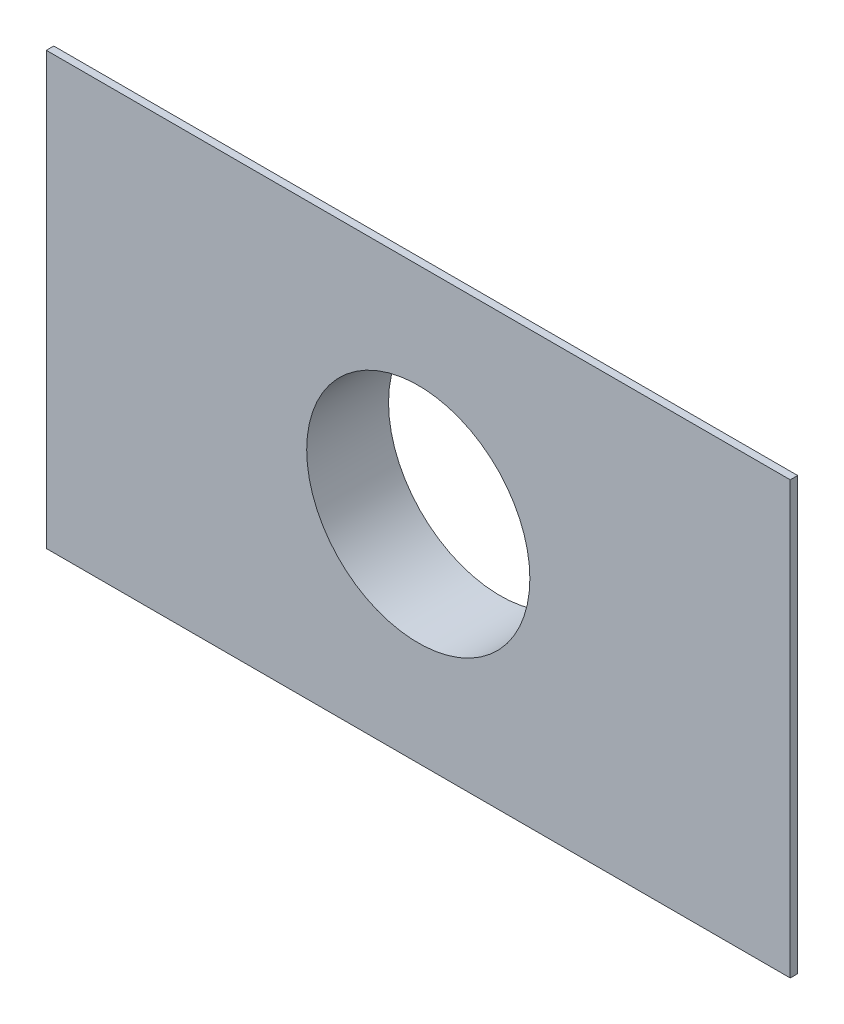
SolidWorks part; units mm, degrees
ref_plane "Front Plane" through (0, 0, 0) normal (0, 0, 1) x (1, 0, 0)
ref_plane "Top Plane" through (0, 0, 0) normal (0, 1, 0) x (1, 0, 0)
ref_plane "Right Plane" through (0, 0, 0) normal (1, 0, 0) x (0, 0, -1)
sketch "Sketch1" plane through (0, 0, 0) normal (0, 0, 1) x (1, 0, 0)
  line L0 (97.6698, 44.8455) -> (-102.3302, 44.8455) construction
  line L1 (-102.3302, 102.8455) -> (97.6698, 102.8455)
  line L2 (-102.3302, 102.8455) -> (-102.3302, -13.1545)
  line L3 (-102.3302, -13.1545) -> (97.6698, -13.1545)
  line L4 (97.6698, 102.8455) -> (97.6698, -13.1545)
  circle A0 centre (-2.3302, 44.8455) radius 30
  dimension "D1" = 60
  dimension "D2" = 116
  dimension "D3" = 200
extrude "Boss-Extrude1" add sketch "Sketch1" along normal blind 2
sketch "Sketch2" plane through (0, 0, 0) normal (0, 0, -1) x (-1, 0, 0)
  circle A0 centre (2.3302, 44.8455) radius 30
  circle A1 centre (2.3302, 44.8455) radius 32
  dimension "D1" = 2
extrude "Boss-Extrude2" add sketch "Sketch2" along normal blind 20
